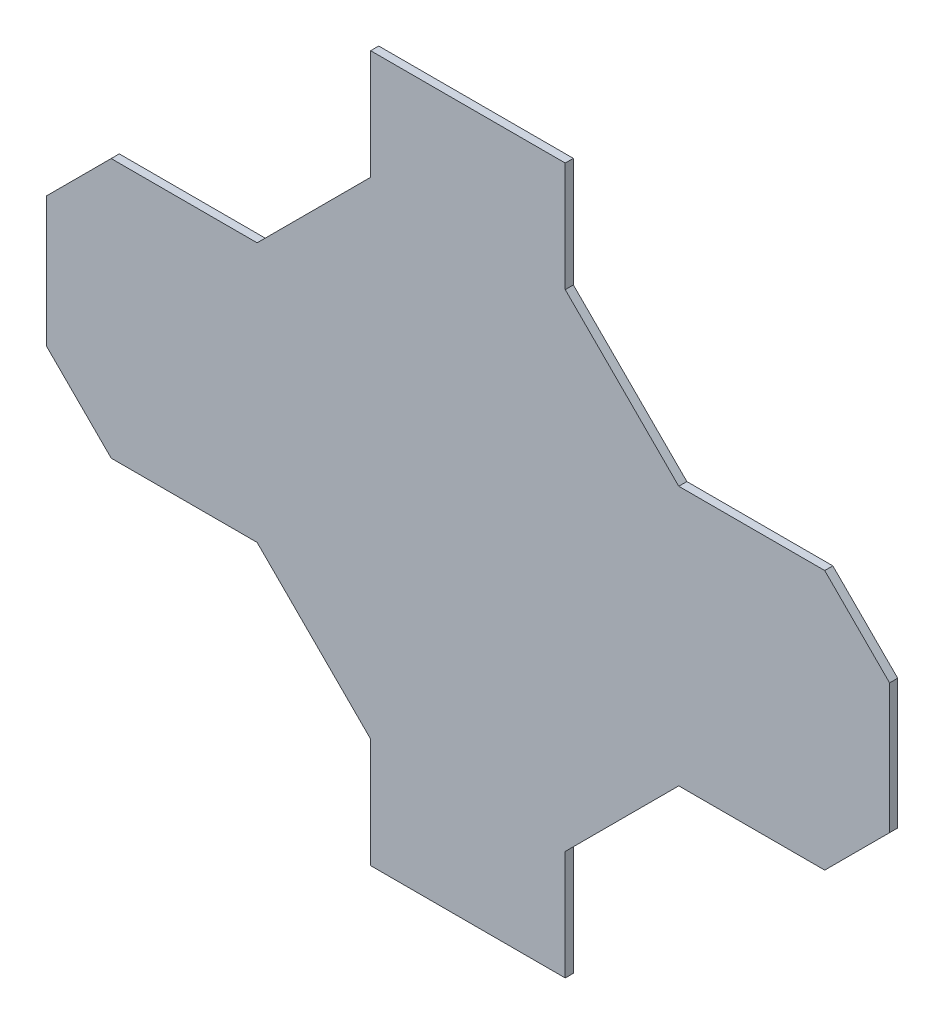
SolidWorks part; units mm, degrees
ref_plane "Front Plane" through (0, 0, 0) normal (0, 0, 1) x (1, 0, 0)
ref_plane "Top Plane" through (0, 0, 0) normal (0, 1, 0) x (1, 0, 0)
ref_plane "Right Plane" through (0, 0, 0) normal (1, 0, 0) x (0, 0, -1)
sketch "Sketch1" plane through (0, 0, 0) normal (0, 0, 1) x (1, 0, 0)
  line L0 (-100, 392.6) -> (100, 392.6) construction
  line L1 (-60, -42.6) -> (60, -42.6)
  line L2 (-60, -42.6) -> (-60, 392.6)
  line L3 (-60, 392.6) -> (60, 392.6)
  line L4 (60, -42.6) -> (60, 392.6)
  line L5 (-60, -42.6) -> (60, 392.6) construction
  line L6 (-60, 392.6) -> (60, -42.6) construction
  line L7 (100, -42.6) -> (-100, -42.6) construction
  line L8 (0, 0) -> (0, 175) construction
  line L10 (-260, 95) -> (260, 95)
  line L11 (-260, 95) -> (-260, 255)
  line L12 (-260, 255) -> (260, 255)
  line L13 (260, 95) -> (260, 255)
  line L14 (-260, 95) -> (260, 255) construction
  line L15 (-260, 255) -> (260, 95) construction
  point P0 (0, 175)
  dimension "D1" = 120
  dimension "D2" = 160
  dimension "D3" = 520
extrude "Boss-Extrude1" add sketch "Sketch1" along normal blind 5 contours L2 L12 L4 L3 | L12 L11 L10 L2 | L12 L2 L10 L4 | L10 L13 L12 L4 | L10 L2 L1 L4
chamfer "Chamfer1" distance 70 angle 45 4 edges at (-60, 255, 2.5) (-60, 95, 2.5) (60, 95, 2.5) (60, 255, 2.5)
chamfer "Chamfer2" distance 40 angle 45 4 edges at (-260, 255, 2.5) (-260, 95, 2.5) (260, 255, 2.5) (260, 95, 2.5)
